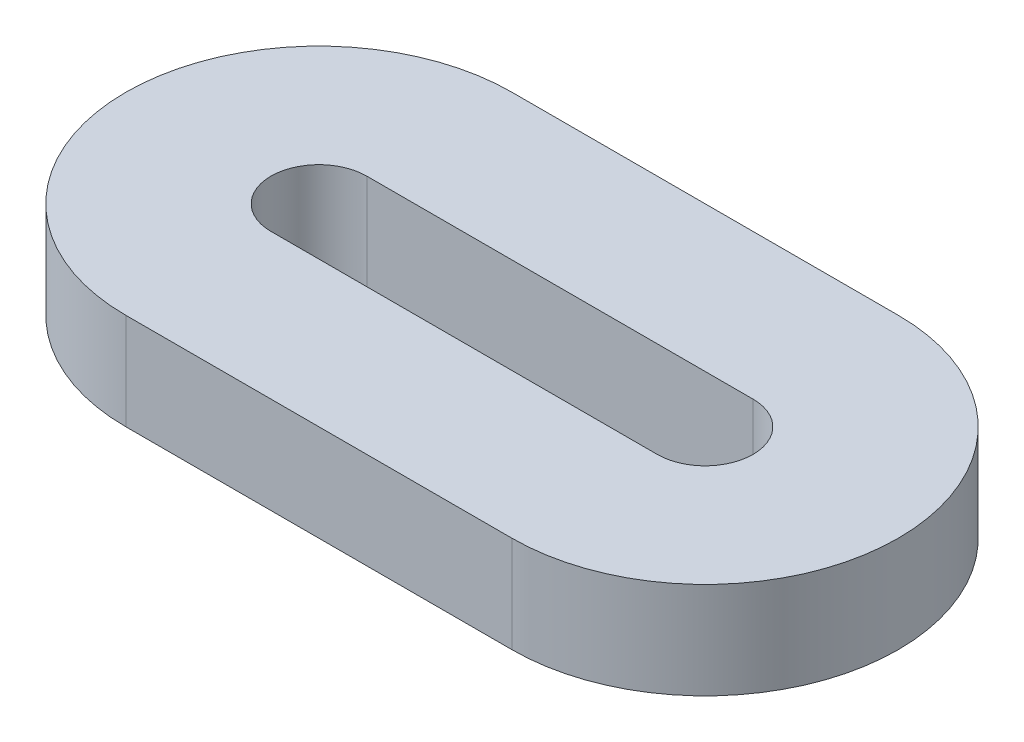
SolidWorks part; units mm, degrees
ref_plane "Front Plane" through (0, 0, 0) normal (0, 0, 1) x (1, 0, 0)
ref_plane "Top Plane" through (0, 0, 0) normal (0, 1, 0) x (1, 0, 0)
ref_plane "Right Plane" through (0, 0, 0) normal (1, 0, 0) x (0, 0, -1)
sketch "Sketch1" plane through (0, 0, 0) normal (0, 1, 0) x (1, 0, 0)
  line L0 (-12.7, 0) -> (12.7, 0) construction
  line L1 (-12.7, 12.7) -> (12.7, 12.7)
  line L2 (-12.7, -12.7) -> (12.7, -12.7)
  line L3 (-12.7, 0) -> (12.7, 0) construction
  line L4 (-12.7, 3.15) -> (12.7, 3.15)
  line L5 (-12.7, -3.15) -> (12.7, -3.15)
  arc A0 (-12.7, 12.7) -> (-12.7, -12.7) centre (-12.7, 0) ccw
  arc A1 (12.7, -12.7) -> (12.7, 12.7) centre (12.7, 0) ccw
  arc A2 (-12.7, 3.15) -> (-12.7, -3.15) centre (-12.7, 0) ccw
  arc A3 (12.7, -3.15) -> (12.7, 3.15) centre (12.7, 0) ccw
  point P2 (0, 0)
  point P10 (0, 0)
  dimension "D2" = 12.7
  dimension "D1" = 25.4
  dimension "D3" = 6.3
extrude "Boss-Extrude1" add sketch "Sketch1" along normal blind 6.35
